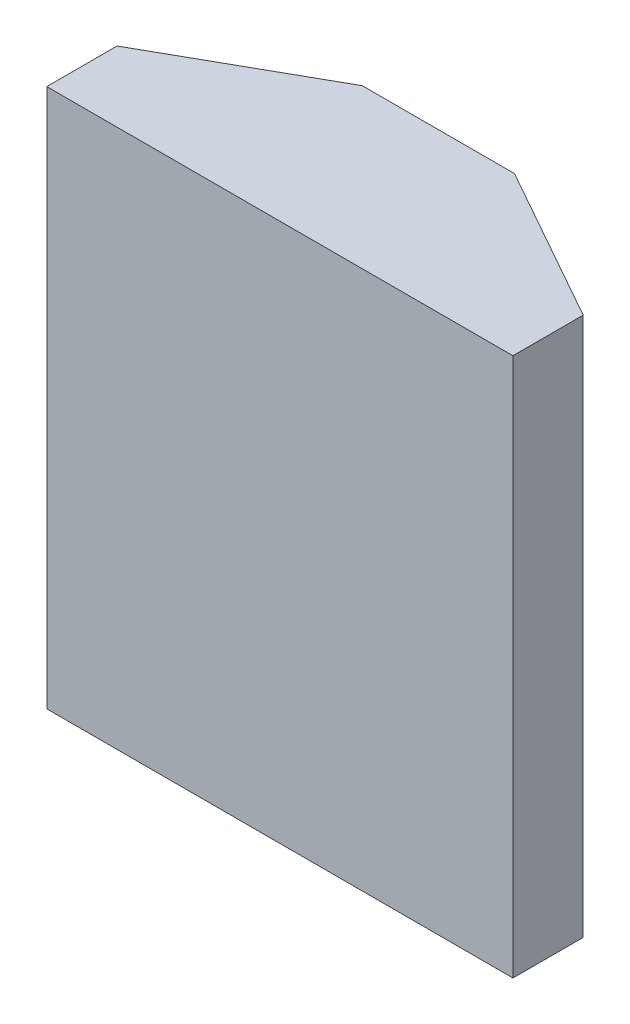
SolidWorks part; units mm, degrees
material "ABS"
ref_plane "Front Plane" through (0, 0, 0) normal (0, 0, 1) x (1, 0, 0)
ref_plane "Top Plane" through (0, 0, 0) normal (0, 1, 0) x (1, 0, 0)
ref_plane "Right Plane" through (0, 0, 0) normal (1, 0, 0) x (0, 0, -1)
sketch "Sketch1" plane through (0, 0, 0) normal (0, 1, 0) x (1, 0, 0)
  line L0 (-19.895, 0) -> (19.895, 0)
  line L1 (19.895, 0) -> (19.895, 6)
  line L2 (19.895, 6) -> (6.5, 13.53)
  line L3 (6.5, 13.53) -> (-6.5, 13.53)
  line L4 (-6.5, 13.53) -> (-19.895, 6)
  line L5 (-19.895, 6) -> (-19.895, 0)
  line L6 (0, 0) -> (0, 13.53) construction
  point P4 (0, 0)
  dimension "D1" = 6
  dimension "D2" = 13
  dimension "D3" = 39.79
  dimension "D4" = 13.53
extrude "Boss-Extrude1" add sketch "Sketch1" along normal blind 46
sketch "Sketch2" plane through (0, 46, 0) normal (0, 1, 0) x (1, 0, 0)
  line L30 (18.895, 5.415) -> (6.2382, 12.53)
  line L31 (18.895, 1) -> (18.895, 5.415)
  line L32 (-18.895, 1) -> (18.895, 1)
  line L33 (-18.895, 5.415) -> (-18.895, 1)
  line L34 (-6.2382, 12.53) -> (-18.895, 5.415)
  line L35 (6.2382, 12.53) -> (-6.2382, 12.53)
  line L36 (18.895, 5.415) -> (6.2382, 12.53)
  line L37 (18.895, 1) -> (18.895, 5.415)
  line L38 (-18.895, 1) -> (18.895, 1)
  line L39 (-18.895, 5.415) -> (-18.895, 1)
  line L40 (-6.2382, 12.53) -> (-18.895, 5.415)
  line L41 (6.2382, 12.53) -> (-6.2382, 12.53)
  dimension "D1" = 1
extrude "Cut-Extrude1" cut sketch "Sketch2" against normal blind 44 from offset 1 offset against normal yes
sketch "Sketch3" plane through (0, 0, 0) normal (0, -1, 0) x (1, 0, 0)
  line L0 (0, 0) -> (0, -13.53) construction
  line L1 (6.5, -13.53) -> (-6.5, -13.53) construction
  line L2 (-2.89, -11.25) -> (2.89, -11.25) construction
  line L3 (-4.17, -12.53) -> (4.17, -12.53) construction
  line L4 (-4.17, -12.53) -> (-4.17, -9.97) construction
  line L5 (-4.17, -9.97) -> (4.17, -9.97) construction
  line L6 (4.17, -12.53) -> (4.17, -9.97) construction
  line L7 (-4.17, -12.53) -> (4.17, -9.97) construction
  line L8 (-4.17, -9.97) -> (4.17, -12.53) construction
  line L9 (-2.89, -9.97) -> (2.89, -9.97)
  line L10 (-2.89, -12.53) -> (2.89, -12.53)
  arc A0 (-2.89, -9.97) -> (-2.89, -12.53) centre (-2.89, -11.25) ccw
  arc A1 (2.89, -12.53) -> (2.89, -9.97) centre (2.89, -11.25) ccw
  point P5 (0, -11.25)
  point P12 (0, -11.25)
  dimension "D1" = 8.34
  dimension "D2" = 2.56
  dimension "D3" = 1
extrude "Cut-Extrude2" cut sketch "Sketch3" against normal up to next
